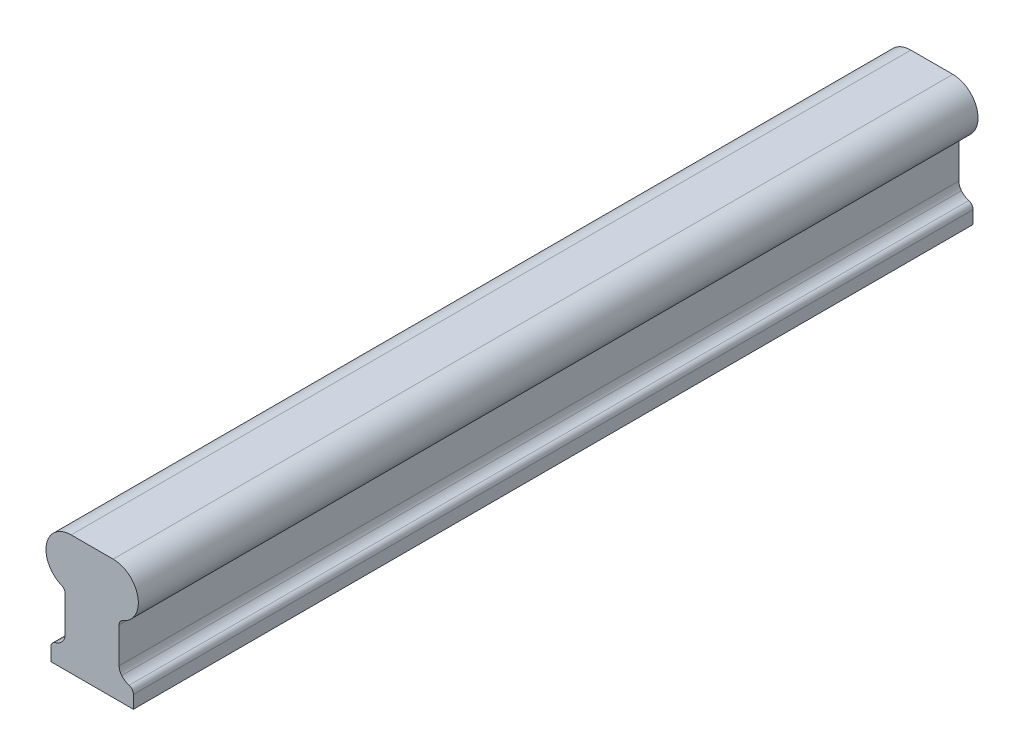
SolidWorks part; units mm, degrees
ref_plane "Front" through (0, 0, 0) normal (0, 0, 1) x (1, 0, 0)
ref_plane "Top" through (0, 0, 0) normal (0, 1, 0) x (1, 0, 0)
ref_plane "Right" through (0, 0, 0) normal (1, 0, 0) x (0, 0, -1)
other "Configuration Table"
sketch "Sketch1" plane through (0, 0, 0) normal (0, 0, 1) x (1, 0, 0)
  line L0 (17.4625, 0) -> (17.4625, 57.9454) construction
  line L1 (0, 0) -> (34.925, 0)
  line L2 (6.0325, 27.94) -> (6.0325, 12.9561)
  line L3 (8.5725, 50.8) -> (26.3525, 50.8)
  line L4 (28.8925, 27.94) -> (28.8925, 12.9561)
  line L5 (0, 0) -> (0, 5.4701)
  line L6 (34.925, 0) -> (34.925, 5.4701)
  arc A0 (8.5725, 50.8) -> (4.4694, 30.2846) centre (8.5725, 40.132) ccw
  arc A1 (26.3525, 50.8) -> (30.4556, 30.2846) centre (26.3525, 40.132) cw
  arc A2 (6.0325, 12.9561) -> (4.9372, 9.9462) centre (1.3493, 12.9561) cw
  arc A3 (28.8925, 12.9561) -> (29.9878, 9.9462) centre (33.5757, 12.9561) ccw
  arc A4 (1.8219, 7.9065) -> (4.9372, 9.9462) centre (0, 14.088) ccw
  arc A5 (33.1031, 7.9065) -> (29.9878, 9.9462) centre (34.925, 14.088) cw
  arc A6 (33.1031, 7.9065) -> (34.925, 5.4701) centre (32.385, 5.4701) cw
  arc A7 (0, 5.4701) -> (1.8219, 7.9065) centre (2.54, 5.4701) cw
  arc A8 (28.8925, 27.94) -> (30.4556, 30.2846) centre (31.4325, 27.94) cw
  arc A9 (4.4694, 30.2846) -> (6.0325, 27.94) centre (3.4925, 27.94) cw
  dimension "D1" = 2.54
  dimension "D2" = 2.54
  dimension "D6" = 10.668
  dimension "D7" = 10.668
  dimension "D3" = 22.86
  dimension "D4" = 50.8
  dimension "D5" = 17.78
  dimension "D8" = 34.925
  dimension "D9" = 27.94
extrude "Base-Extrude" add sketch "Sketch1" along normal blind 355.6
